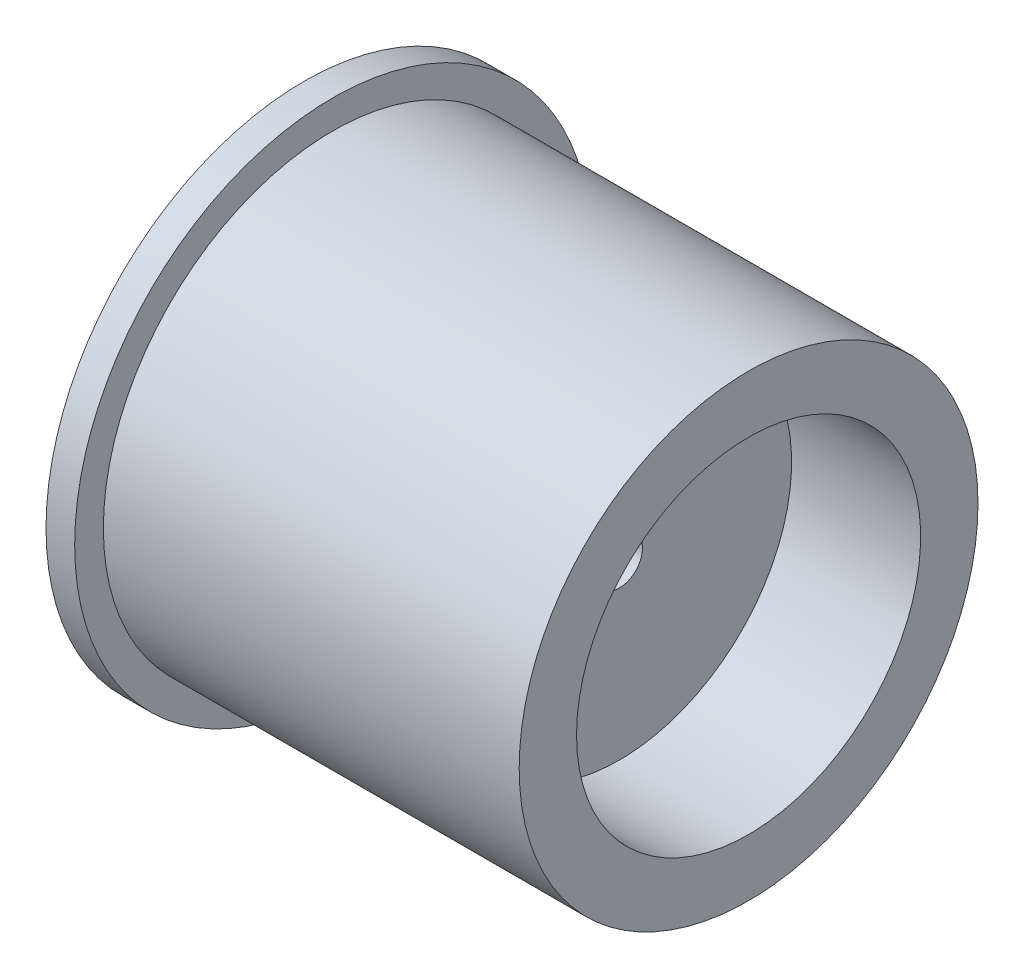
SolidWorks part; units mm, degrees
material "ABS"
ref_plane "Front Plane" through (0, 0, 0) normal (0, 0, 1) x (1, 0, 0)
ref_plane "Top Plane" through (0, 0, 0) normal (0, 1, 0) x (1, 0, 0)
ref_plane "Right Plane" through (0, 0, 0) normal (1, 0, 0) x (0, 0, -1)
sketch "Sketch3" plane through (0, 0, 0) normal (0, 0, 1) x (1, 0, 0)
  line L0 (0, 0) -> (18, 0) construction
  line L1 (-7, 1.6) -> (6, 1.6)
  line L2 (6, 1.6) -> (6, 12)
  line L6 (15, 12) -> (15, 16)
  line L7 (15, 16) -> (-14, 16)
  line L9 (-16, 13) -> (-7, 13)
  line L10 (-7, 13) -> (-7, 1.6)
  line L11 (15, 12) -> (6, 12)
  line L12 (-16, 18) -> (-16, 13)
  line L15 (-16, 18) -> (-14, 18)
  line L16 (-14, 16) -> (-14, 18)
  dimension "D1" = 3.2
  dimension "D2" = 9
  dimension "D3" = 32
  dimension "D4" = 31
  dimension "D5" = 13
  dimension "D6" = 18
  dimension "D7" = 24
  dimension "D8" = 3
  dimension "D9" = 3
  dimension "D10" = 2
  dimension "D11" = 2
revolve "Revolve1" add sketch "Sketch3" angle 360 about L0
sketch "Sketch4" plane through (0, 0, 0) normal (1, 0, 0) x (0, 0, -1)
  line L1 (3.6084, 6.25) -> (-3.6084, 6.25)
  line L2 (-3.6084, 6.25) -> (-7.2169, 0)
  line L3 (-7.2169, 0) -> (-3.6084, -6.25)
  line L4 (-3.6084, -6.25) -> (3.6084, -6.25)
  line L5 (3.6084, -6.25) -> (7.2169, 0)
  line L6 (7.2169, 0) -> (3.6084, 6.25)
  circle A0 centre (0, 0) radius 6.25 construction
  point P15 (0, 6.25)
  dimension "D1" = 12.5
extrude "Cut-Extrude1" cut sketch "Sketch4" along normal blind 6 from surface at -7 starting at face at (-7, 0, 1.6)
